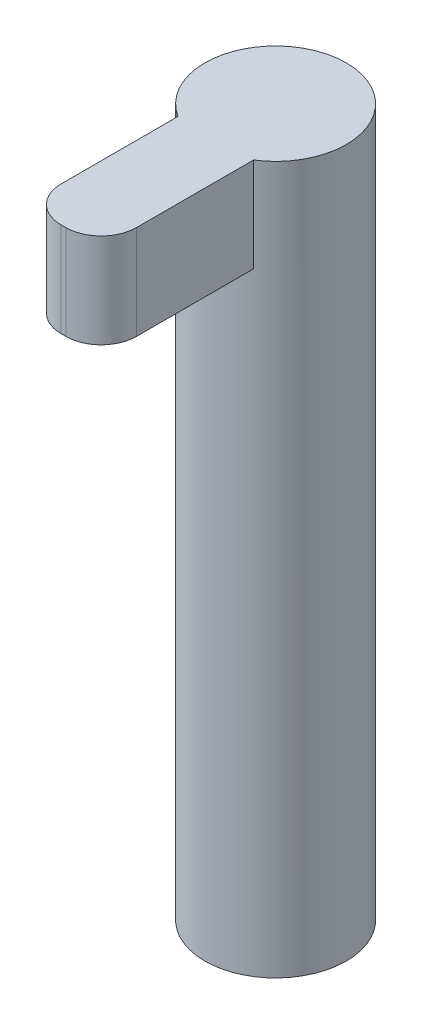
SolidWorks part; units mm, degrees
ref_plane "Alzado" through (0, 0, 0) normal (0, 0, 1) x (1, 0, 0)
ref_plane "Planta" through (0, 0, 0) normal (0, 1, 0) x (1, 0, 0)
ref_plane "Vista lateral" through (0, 0, 0) normal (1, 0, 0) x (0, 0, -1)
sketch "Croquis1" plane through (0, 0, 0) normal (0, 1, 0) x (1, 0, 0)
  circle A0 centre (0, 0) radius 3
  dimension "D1" = 6
extrude "Saliente-Extruir1" add sketch "Croquis1" along normal blind 30
sketch "Croquis2" plane through (0, 0, 0) normal (0, 0, 1) x (1, 0, 0)
  line L1 (3, 30) -> (-3, 30) construction
  line L3 (-1.6007, 26) -> (1.6007, 26)
  line L4 (1.6007, 26) -> (1.6007, 30)
  line L5 (-1.6007, 26) -> (-1.6007, 30)
  line L6 (-1.6007, 30) -> (1.6007, 30)
  point P5 (0, 40)
  dimension "D1" = 4
extrude "Saliente-Extruir2" add sketch "Croquis2" along normal blind 9
fillet "Redondeo2" radius 1.5 2 edges at (-1.6007, 28, 9) (1.6007, 28, 9)
